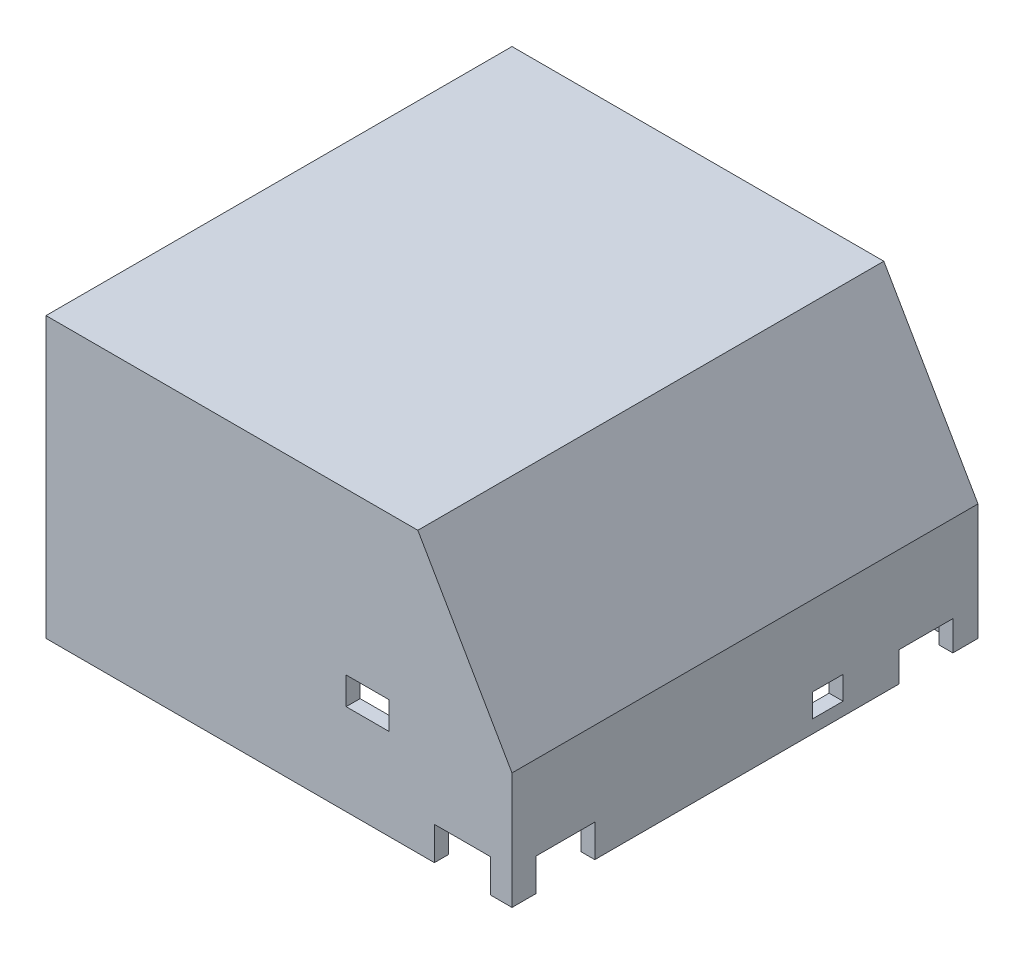
SolidWorks part; units mm, degrees
ref_plane "Front Plane" through (0, 0, 0) normal (0, 0, 1) x (1, 0, 0)
ref_plane "Top Plane" through (0, 0, 0) normal (0, 1, 0) x (1, 0, 0)
ref_plane "Right Plane" through (0, 0, 0) normal (1, 0, 0) x (0, 0, -1)
sketch "Sketch1" plane through (0, 0, 0) normal (0, 0, 1) x (1, 0, 0)
  line L0 (-50, 12.5) -> (-50, 47.5)
  line L1 (-50, -12.5) -> (50, -12.5)
  line L2 (-50, -12.5) -> (-50, 12.5)
  line L3 (-50, 12.5) -> (50, 12.5) construction
  line L4 (50, -12.5) -> (50, 12.5)
  line L5 (-50, -12.5) -> (50, 12.5) construction
  line L6 (-50, 12.5) -> (50, -12.5) construction
  line L7 (-50, 47.5) -> (29.7927, 47.5)
  line L8 (29.7927, 47.5) -> (50, 12.5)
  point P0 (0, 0)
  dimension "D1" = 100
  dimension "D2" = 25
  dimension "D3" = 60
  dimension "D4" = 60
extrude "Boss-Extrude1" add sketch "Sketch1" along normal blind 100 contours L8 L4 L1 L2 L0 L7
shell "Shell1" thickness 3
sketch "Sketch2" plane through (-50, 0, 0) normal (-1, 0, 0) x (0, 0, 1)
  line L0 (100, -12.5) -> (0, -12.5) construction
  line L1 (23.8769, -12.5) -> (79.8925, -12.5)
  line L2 (23.8769, -12.5) -> (23.8769, 22.5)
  line L3 (23.8769, 22.5) -> (79.8925, 22.5)
  line L4 (79.8925, -12.5) -> (79.8925, 22.5)
  line L5 (23.8769, -12.5) -> (79.8925, 22.5) construction
  line L6 (23.8769, 22.5) -> (79.8925, -12.5) construction
  point P4 (51.8847, 5)
  dimension "D1" = 35
extrude "Cut-Extrude1" cut sketch "Sketch2" against normal blind 10
sketch "Sketch3" plane through (50, 0, 0) normal (1, 0, 0) x (0, 0, -1)
  line L0 (-50.3131, -12.5) -> (-50.3131, 6.4865) construction
  line L1 (-100, -12.5) -> (0, -12.5) construction
  line L3 (-94.8455, -12.5) -> (-82.2389, -12.5)
  line L4 (-94.8455, -12.5) -> (-94.8455, -5.5198)
  line L5 (-94.8455, -5.5198) -> (-82.2389, -5.5198)
  line L6 (-82.2389, -12.5) -> (-82.2389, -5.5198)
  line L7 (-94.8455, -12.5) -> (-82.2389, -5.5198) construction
  line L8 (-94.8455, -5.5198) -> (-82.2389, -12.5) construction
  line L9 (-5.3987, -12.5) -> (-16.9138, -12.5)
  line L10 (-5.3987, -12.5) -> (-5.3987, -6.1201)
  line L11 (-5.3987, -6.1201) -> (-16.9138, -6.1201)
  line L12 (-16.9138, -12.5) -> (-16.9138, -6.1201)
  line L13 (-5.3987, -12.5) -> (-16.9138, -6.1201) construction
  line L14 (-5.3987, -6.1201) -> (-16.9138, -12.5) construction
  point P8 (-88.5422, -9.0099)
  point P13 (-11.1563, -9.3101)
extrude "Cut-Extrude2" cut sketch "Sketch3" against normal blind 10
sketch "Sketch4" plane through (0, 0, 100) normal (0, 0, 1) x (1, 0, 0)
  line L1 (14.4088, 12.9154) -> (23.578, 12.9154)
  line L2 (14.4088, 12.9154) -> (14.4088, 7.0209)
  line L3 (14.4088, 7.0209) -> (23.578, 7.0209)
  line L4 (23.578, 12.9154) -> (23.578, 7.0209)
  line L5 (14.4088, 12.9154) -> (23.578, 7.0209) construction
  line L6 (14.4088, 7.0209) -> (23.578, 12.9154) construction
  point P4 (18.9934, 9.9681)
extrude "Cut-Extrude3" cut sketch "Sketch4" against normal blind 10
sketch "Sketch5" plane through (-50, 0, 0) normal (-1, 0, 0) x (0, 0, 1)
  line L0 (50, 47.5) -> (50, 18.7219) construction
  line L1 (5.2219, -4.6054) -> (11.9979, -4.6054)
  line L2 (5.2219, -4.6054) -> (5.2219, -9.6596)
  line L3 (5.2219, -9.6596) -> (11.9979, -9.6596)
  line L4 (11.9979, -4.6054) -> (11.9979, -9.6596)
  line L5 (5.2219, -4.6054) -> (11.9979, -9.6596) construction
  line L6 (5.2219, -9.6596) -> (11.9979, -4.6054) construction
  line L11 (100, 47.5) -> (0, 47.5) construction
  line L12 (94.7781, -9.6596) -> (88.0021, -9.6596)
  line L13 (88.0021, -4.6054) -> (88.0021, -9.6596)
  line L14 (94.7781, -4.6054) -> (88.0021, -4.6054)
  line L15 (94.7781, -4.6054) -> (94.7781, -9.6596)
  point P4 (8.6099, -7.1325)
extrude "Cut-Extrude4" cut sketch "Sketch5" against normal blind 10
sketch "Sketch6" plane through (0, 0, 100) normal (0, 0, 1) x (1, 0, 0)
  line L0 (-50, -12.5) -> (50, -12.5) construction
  line L1 (45.3423, -12.5) -> (33.3518, -12.5)
  line L2 (45.3423, -12.5) -> (45.3423, -5.3727)
  line L3 (45.3423, -5.3727) -> (33.3518, -5.3727)
  line L4 (33.3518, -12.5) -> (33.3518, -5.3727)
  line L5 (45.3423, -12.5) -> (33.3518, -5.3727) construction
  line L6 (45.3423, -5.3727) -> (33.3518, -12.5) construction
  point P4 (39.3471, -8.9363)
extrude "Cut-Extrude5" cut sketch "Sketch6" against normal blind 10
sketch "Sketch8" plane through (50, 0, 0) normal (1, 0, 0) x (0, 0, -1)
  line L1 (-35.5126, -9.6977) -> (-28.9496, -9.6977)
  line L2 (-35.5126, -9.6977) -> (-35.5126, -4.692)
  line L3 (-35.5126, -4.692) -> (-28.9496, -4.692)
  line L4 (-28.9496, -9.6977) -> (-28.9496, -4.692)
  line L5 (-35.5126, -9.6977) -> (-28.9496, -4.692) construction
  line L6 (-35.5126, -4.692) -> (-28.9496, -9.6977) construction
  point P4 (-32.2311, -7.1948)
extrude "Cut-Extrude6" cut sketch "Sketch8" against normal blind 10
